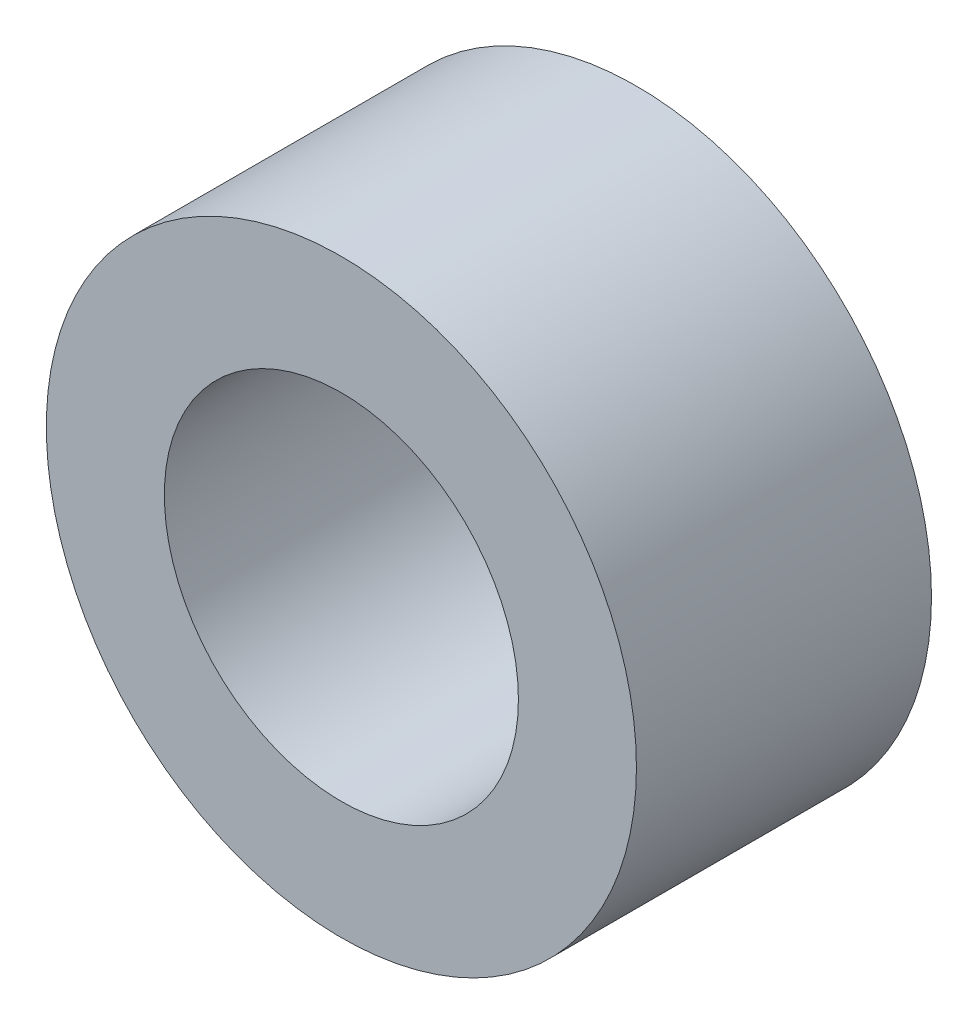
SolidWorks part; units mm, degrees
material "尼龙 101"
ref_plane "前视基准面" through (0, 0, 0) normal (0, 0, 1) x (1, 0, 0)
ref_plane "上视基准面" through (0, 0, 0) normal (0, 1, 0) x (1, 0, 0)
ref_plane "右视基准面" through (0, 0, 0) normal (1, 0, 0) x (0, 0, -1)
other "Configuration Table"
sketch "草图1" plane through (0, 0, 0) normal (0, 0, 1) x (1, 0, 0)
  circle A0 centre (0, 0) radius 1.5
  circle A1 centre (0, 0) radius 2.5
  dimension "D1" = 3
  dimension "D2" = 5
extrude "凸台-拉伸1" add sketch "草图1" along normal blind 2.5
